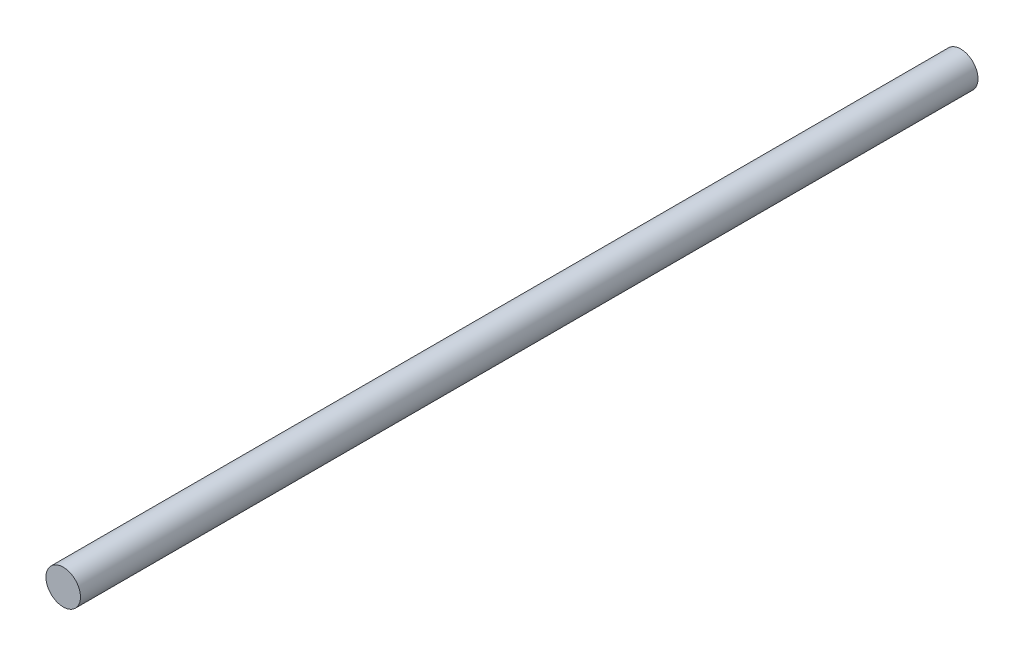
SolidWorks part; units mm, degrees
ref_plane "Front Plane" through (0, 0, 0) normal (0, 0, 1) x (1, 0, 0)
ref_plane "Top Plane" through (0, 0, 0) normal (0, 1, 0) x (1, 0, 0)
ref_plane "Right Plane" through (0, 0, 0) normal (1, 0, 0) x (0, 0, -1)
sketch "Sketch1" plane through (0, 0, 0) normal (0, 0, 1) x (1, 0, 0)
  circle A0 centre (0, 0) radius 5
  dimension "D1" = 10
extrude "Boss-Extrude1" add sketch "Sketch1" along normal blind 250
sketch "Sketch2" plane through (0, 0, 250) normal (0, 0, 1) x (1, 0, 0)
  circle A1 centre (0, 0) radius 5
  circle A2 centre (0, 0) radius 5
  dimension "D1" = 0
extrude "Boss-Extrude2" add sketch "Sketch2" along normal blind 10
